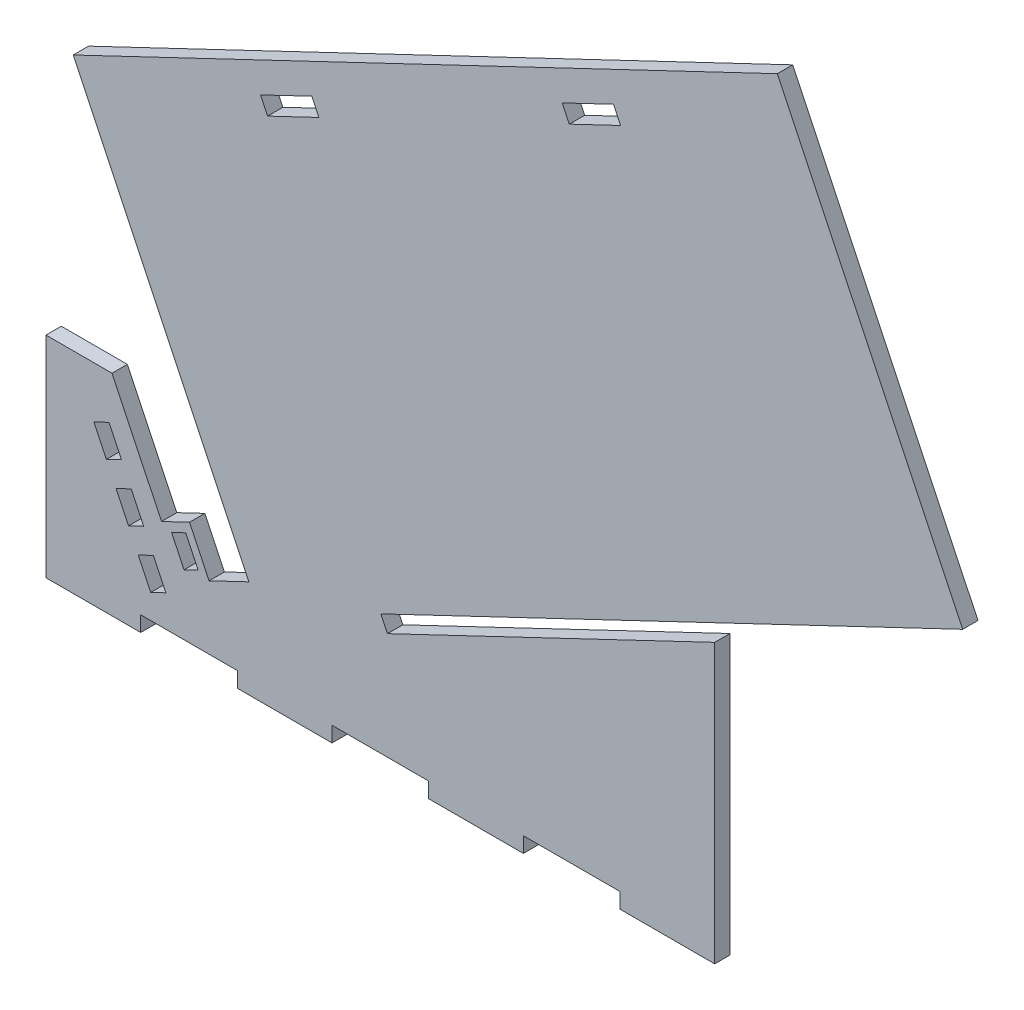
SolidWorks part; units mm, degrees
ref_plane "Front Plane" through (0, 0, 0) normal (0, 0, 1) x (1, 0, 0)
ref_plane "Top Plane" through (0, 0, 0) normal (0, 1, 0) x (1, 0, 0)
ref_plane "Right Plane" through (0, 0, 0) normal (1, 0, 0) x (0, 0, -1)
sketch "Sketch1" plane through (0, 0, 0) normal (0, 0, 1) x (1, 0, 0)
  line L12 (-264.2572, -95.6581) -> (-230.2572, -95.6581)
  line L13 (-230.2572, -95.6581) -> (-230.2572, -90.1581)
  line L15 (-264.2572, -90.1581) -> (-264.2572, -95.6581)
  line L24 (-241.7419, -36.2998) -> (-237.4367, -45.3257)
  line L25 (-237.4367, -45.3257) -> (-242.4912, -47.7366)
  line L26 (-242.4912, -47.7366) -> (-246.7963, -38.7107)
  line L27 (-246.7963, -38.7107) -> (-241.7419, -36.2998)
  line L28 (-233.7774, -52.9977) -> (-229.4723, -62.0235)
  line L29 (-229.4723, -62.0235) -> (-234.5268, -64.4344)
  line L30 (-234.5268, -64.4344) -> (-238.8319, -55.4085)
  line L31 (-238.8319, -55.4085) -> (-233.7774, -52.9977)
  line L32 (-225.8129, -69.6955) -> (-221.5078, -78.7214)
  line L33 (-221.5078, -78.7214) -> (-226.5623, -81.1322)
  line L34 (-226.5623, -81.1322) -> (-230.8674, -72.1064)
  line L35 (-230.8674, -72.1064) -> (-225.8129, -69.6955)
  line L44 (-195.5972, -95.6581) -> (-161.5972, -95.6581)
  line L45 (-195.5972, -90.1581) -> (-195.5972, -95.6581)
  line L47 (-161.5972, -95.6581) -> (-161.5972, -90.1581)
  line L52 (-24.2572, -95.6581) -> (-58.2572, -95.6581)
  line L53 (-58.2572, -95.6581) -> (-58.2572, -90.1581)
  line L55 (-24.2572, -90.1581) -> (-24.2572, -95.6581)
  line L56 (-92.9172, -95.6581) -> (-126.9172, -95.6581)
  line L57 (-126.9172, -95.6581) -> (-126.9172, -90.1581)
  line L59 (-92.9172, -90.1581) -> (-92.9172, -95.6581)
  line L61 (-264.2572, -90.1581) -> (-264.2572, -20.2081)
  line L62 (-264.2572, -20.2081) -> (-240.5538, -20.2081)
  line L63 (-240.5538, -20.2081) -> (-222.803, -57.4233)
  line L64 (-205.7265, -67.3163) -> (-191.4241, -60.4944)
  line L65 (-191.4241, -60.4944) -> (-254.494, 71.7343)
  line L66 (-230.2572, -90.1581) -> (-195.5972, -90.1581)
  line L67 (-161.5972, -90.1581) -> (-126.9172, -90.1581)
  line L68 (-58.2572, -90.1581) -> (-92.9172, -90.1581)
  line L70 (-254.494, 71.7343) -> (-1.7701, 192.2774)
  line L71 (-219.5705, -82.783) -> (-144.0757, -46.7738) construction
  line L80 (-78.6977, 144.5056) -> (-60.646, 153.1158)
  line L81 (-60.646, 153.1158) -> (-58.2782, 148.1516)
  line L82 (-58.2782, 148.1516) -> (-76.3299, 139.5414)
  line L83 (-76.3299, 139.5414) -> (-78.6977, 144.5056)
  line L84 (-187.0079, 92.8442) -> (-168.9562, 101.4545)
  line L85 (-168.9562, 101.4545) -> (-166.5884, 96.4902)
  line L86 (-166.5884, 96.4902) -> (-184.6401, 87.88)
  line L87 (-184.6401, 87.88) -> (-187.0079, 92.8442)
  line L88 (-24.2572, -90.1581) -> (-24.2572, 4.2831)
  line L89 (-144.0757, -46.7738) -> (-141.7079, -51.738)
  line L92 (-141.7079, -51.738) -> (-24.2572, 4.2831)
  line L93 (-144.0757, -46.7738) -> (64.7438, 52.828)
  line L94 (64.7438, 52.828) -> (-1.7701, 192.2774)
  line L106 (-237.1701, -45.4201) -> (-242.5856, -48.0032)
  line L107 (-242.5856, -48.0032) -> (-247.063, -38.6163)
  line L108 (-247.063, -38.6163) -> (-241.6474, -36.0332)
  line L109 (-241.6474, -36.0332) -> (-237.1701, -45.4201)
  line L110 (-229.2057, -62.1179) -> (-234.6212, -64.701)
  line L111 (-234.6212, -64.701) -> (-239.0985, -55.3141)
  line L112 (-239.0985, -55.3141) -> (-233.683, -52.7311)
  line L113 (-233.683, -52.7311) -> (-229.2057, -62.1179)
  line L114 (-231.134, -72.012) -> (-225.7185, -69.4289)
  line L115 (-225.7185, -69.4289) -> (-221.2412, -78.8158)
  line L116 (-221.2412, -78.8158) -> (-226.6567, -81.3988)
  line L117 (-226.6567, -81.3988) -> (-231.134, -72.012)
  line L118 (-166.3218, 96.3958) -> (-184.7345, 87.6134)
  line L119 (-184.7345, 87.6134) -> (-187.2746, 92.9387)
  line L120 (-187.2746, 92.9387) -> (-168.8618, 101.7211)
  line L121 (-168.8618, 101.7211) -> (-166.3218, 96.3958)
  line L122 (-58.0116, 148.0572) -> (-76.4243, 139.2747)
  line L123 (-76.4243, 139.2747) -> (-78.9643, 144.6)
  line L124 (-78.9643, 144.6) -> (-60.5516, 153.3824)
  line L125 (-60.5516, 153.3824) -> (-58.0116, 148.0572)
  line L126 (-222.803, -57.4233) -> (-212.7356, -52.6214)
  line L127 (-212.7356, -52.6214) -> (-205.7265, -67.3163)
  line L128 (-219.2063, -59.0316) -> (-214.1518, -56.6207)
  line L129 (-214.1518, -56.6207) -> (-209.6745, -66.0076)
  line L130 (-209.6745, -66.0076) -> (-214.729, -68.4185)
  line L131 (-214.729, -68.4185) -> (-219.2063, -59.0316)
  dimension "D3" = 8
  dimension "D4" = 8
  dimension "D6" = 10
  dimension "D9" = 10.4
extrude "Boss-Extrude1" add sketch "Sketch1" along normal blind 5.5 contours L93 L94 L70 L65 L64 L63 L62 L61 L15 L12 L13 L66 L45 L44 L47 L67 L57 L56 L59 L68 L53 L52 L55 L88 L92 L89 L120 L121 L118 L119 L112 L113 L110 L111 L108 L109 L106 L107 L116 L117 L114 L115 L124 L125 L122 L123
